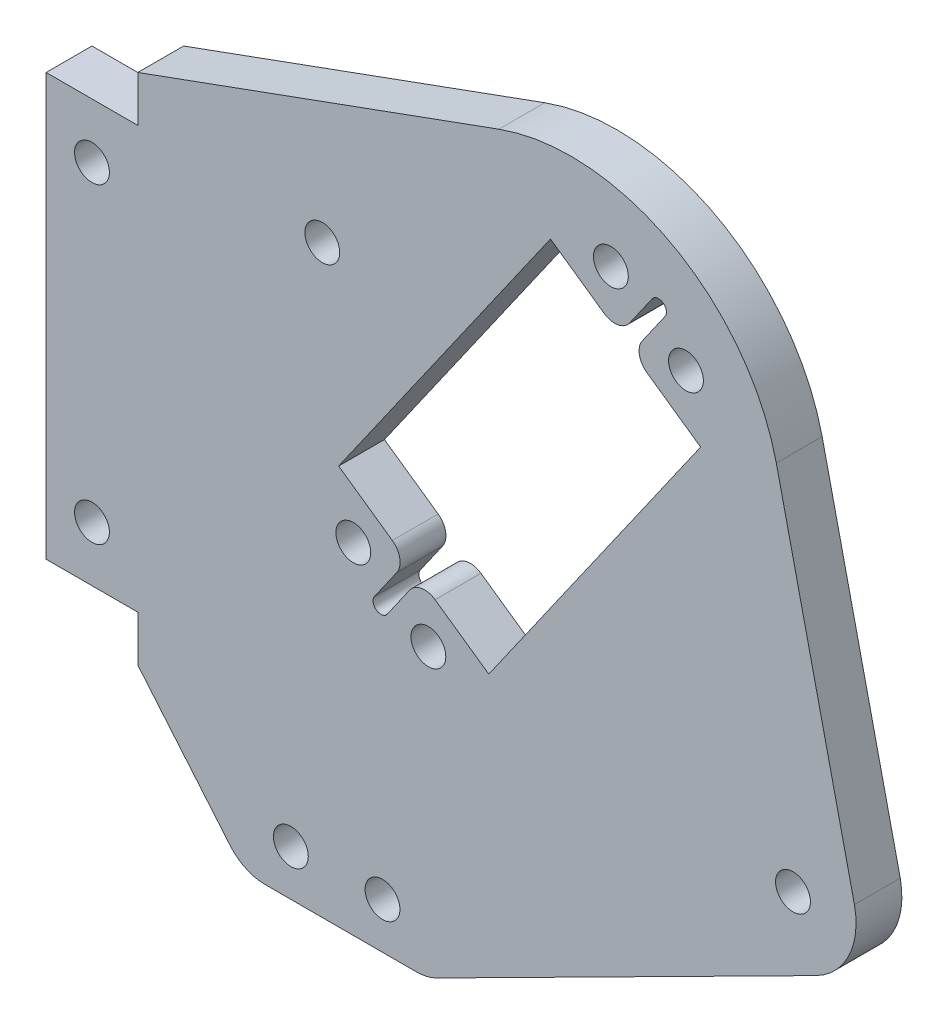
SolidWorks part; units mm, degrees
ref_plane "Plan de face" through (0, 0, 0) normal (0, 0, 1) x (1, 0, 0)
ref_plane "Plan de dessus" through (0, 0, 0) normal (0, 1, 0) x (1, 0, 0)
ref_plane "Plan de droite" through (0, 0, 0) normal (1, 0, 0) x (0, 0, -1)
sketch "Esquisse1" plane through (0, 0, 0) normal (0, 0, 1) x (1, 0, 0)
  line L4 (40.5483, -21.2763) -> (-0.9757, -42.2648)
  line L5 (36.1516, 24.9571) -> (44.6728, -12.5054)
  line L6 (-33.5199, 27.0306) -> (5.8805, 41.3711)
  line L7 (-33.5199, 22.0306) -> (-33.5199, 27.0306)
  line L8 (-43.5199, 22.0306) -> (-33.5199, 22.0306)
  line L9 (-43.5199, -23.9694) -> (-43.5199, 22.0306)
  line L10 (-33.5199, -23.9694) -> (-43.5199, -23.9694)
  line L11 (-33.5199, -28.9679) -> (-33.5199, -23.9694)
  line L12 (-23.3834, -41.0481) -> (-33.5199, -28.9679)
  line L13 (-3.1416, -42.7582) -> (-19.6182, -42.7582)
  line L20 (-82.9727, -0.9694) -> (-33.257, -0.9694) construction
  line L32 (21.6173, 29.3287) -> (24.055, 32.8101)
  line L33 (22.6253, 33.7321) -> (20.1876, 30.2507)
  line L34 (17.3664, 29.7067) -> (11.5086, 33.8084)
  line L35 (11.5086, 33.8084) -> (-11.6065, 0.7965)
  line L36 (-11.6065, 0.7965) -> (-5.7496, -3.3045)
  line L37 (-5.2585, -6.09) -> (-7.6962, -9.5714)
  line L38 (-6.3036, -10.5465) -> (-3.8659, -7.0651)
  line L39 (-1.0804, -6.5739) -> (4.7765, -10.675)
  line L40 (4.7765, -10.675) -> (27.8916, 22.3368)
  line L41 (27.8916, 22.3368) -> (22.0313, 26.4403)
  circle A0 centre (37.9685, -14.6462) radius 1.9
  circle A2 centre (26.2909, 28.768) radius 1.9
  circle A3 centre (18.0994, 34.5038) radius 1.9
  circle A4 centre (-1.8143, -11.3704) radius 1.9
  circle A5 centre (-10.0058, -5.6346) radius 1.9
  circle A6 centre (-13.3885, 21.0306) radius 1.9
  circle A7 centre (-6.8184, -37.7582) radius 1.9
  circle A8 centre (-16.8184, -37.7582) radius 1.9
  arc A9 (-3.1416, -42.7582) -> (-0.9757, -42.2648) centre (-3.1416, -37.7582) ccw
  arc A10 (40.5483, -21.2763) -> (44.6728, -12.5054) centre (36.8505, -14.1822) ccw
  arc A11 (36.1516, 24.9571) -> (5.8805, 41.3711) centre (13.7469, 19.7582) ccw
  arc A12 (-23.3834, -41.0481) -> (-19.6182, -42.7582) centre (-19.6182, -37.7582) ccw
  circle A13 centre (-38.5199, -17.9694) radius 1.9
  circle A14 centre (-38.5199, 16.0306) radius 1.9
  arc A26 (24.055, 32.8101) -> (22.6253, 33.7321) centre (23.3042, 33.2154) ccw
  arc A27 (17.3664, 29.7067) -> (20.1876, 30.2507) centre (18.5135, 31.345) ccw
  arc A28 (-5.2585, -6.09) -> (-5.7496, -3.3045) centre (-6.8968, -4.9428) ccw
  arc A29 (-7.6962, -9.5714) -> (-6.3036, -10.5465) centre (-6.9999, -10.0589) ccw
  arc A30 (-1.0804, -6.5739) -> (-3.8659, -7.0651) centre (-2.2276, -8.2122) ccw
  arc A31 (21.6173, 29.3287) -> (22.0313, 26.4403) centre (23.1784, 28.0786) ccw
  dimension "D1" = 3.8
  dimension "D2" = 23
  dimension "D3" = 8
  dimension "D4" = 5
  dimension "D7" = 6
  dimension "D8" = 6
  dimension "D12" = 5
  dimension "D5" = 46
  dimension "D6" = 23
  dimension "D9" = 5
  dimension "D10" = 110
  dimension "D11" = 140
  dimension "D13" = 20
  dimension "D14" = 40.3
  dimension "D15" = 1.7
  dimension "D16" = 10
extrude "Boss.-Extru.1" add sketch "Esquisse1" along normal blind 5
